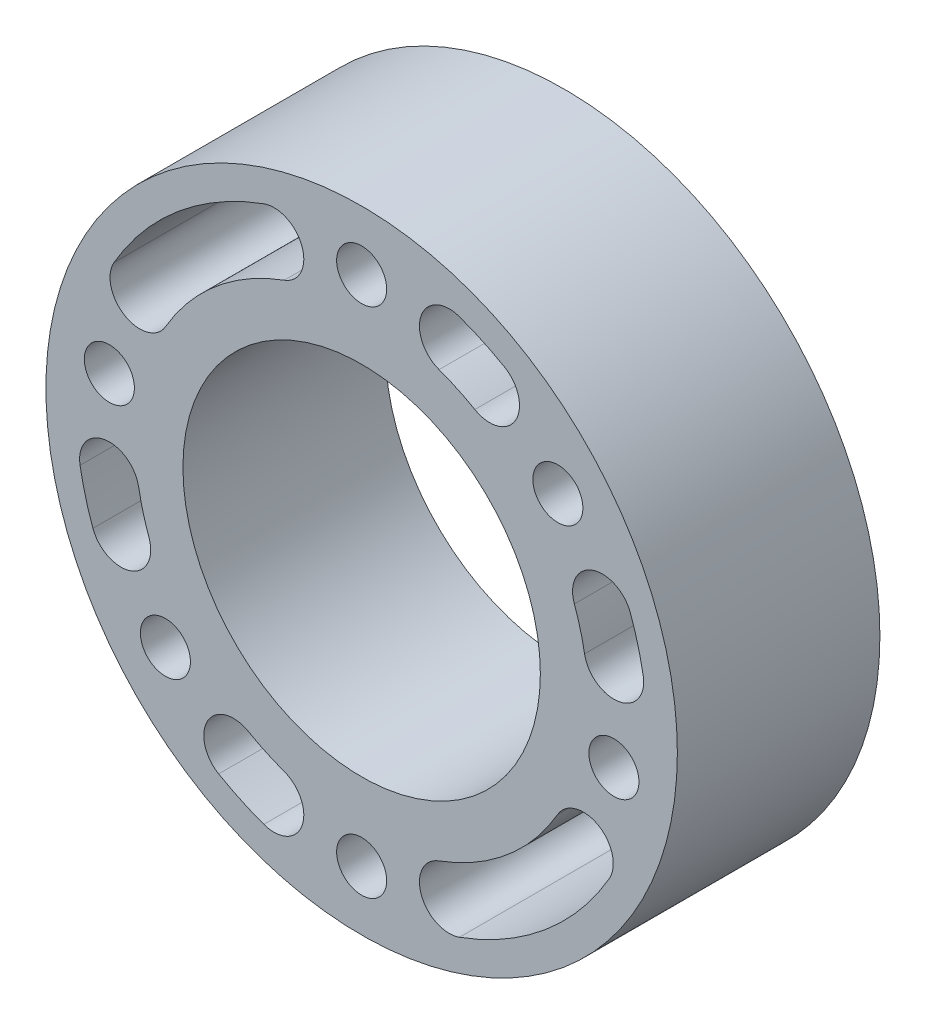
SolidWorks part; units mm, degrees
material "6061 合金"
ref_plane "前视基准面" through (0, 0, 0) normal (0, 0, 1) x (1, 0, 0)
ref_plane "上视基准面" through (0, 0, 0) normal (0, 1, 0) x (1, 0, 0)
ref_plane "右视基准面" through (0, 0, 0) normal (1, 0, 0) x (0, 0, -1)
sketch "草图1" plane through (0, 0, 0) normal (0, 0, 1) x (1, 0, 0)
  circle A0 centre (0, 0) radius 15
  circle A1 centre (0, 0) radius 26.5
  circle A2 centre (0, 0) radius 21.5 construction
  circle A3 centre (0, 21.5) radius 2.1
  circle A4 centre (16.47, 13.8199) radius 2.1
  circle A5 centre (21.1734, -3.7334) radius 2.1
  circle A6 centre (0, -21.5) radius 2.1
  circle A7 centre (-16.47, -13.8199) radius 2.1
  circle A8 centre (-21.1734, 3.7334) radius 2.1
  arc A9 (-18.6195, 10.75) -> (-7.3534, 20.2034) centre (0, 0) cw construction
  arc A10 (-8.2085, 22.5526) -> (-20.7846, 12) centre (0, 0) ccw
  arc A11 (-6.4984, 17.8542) -> (-16.4545, 9.5) centre (0, 0) ccw
  arc A12 (-6.4984, 17.8542) -> (-8.2085, 22.5526) centre (-7.3534, 20.2034) ccw
  arc A13 (-20.7846, 12) -> (-16.4545, 9.5) centre (-18.6195, 10.75) ccw
  arc A14 (7.3534, 20.2034) -> (10.75, 18.6195) centre (0, 0) cw construction
  arc A15 (12, 20.7846) -> (8.2085, 22.5526) centre (0, 0) ccw
  arc A16 (9.5, 16.4545) -> (6.4984, 17.8542) centre (0, 0) ccw
  arc A17 (9.5, 16.4545) -> (12, 20.7846) centre (10.75, 18.6195) ccw
  arc A18 (8.2085, 22.5526) -> (6.4984, 17.8542) centre (7.3534, 20.2034) ccw
  arc A19 (18.7113, 3.2993) -> (17.8542, 6.4984) centre (0, 0) ccw
  arc A20 (18.7113, 3.2993) -> (23.6354, 4.1676) centre (21.1734, 3.7334) ccw
  arc A21 (22.5526, 8.2085) -> (17.8542, 6.4984) centre (20.2034, 7.3534) ccw
  arc A22 (23.6354, 4.1676) -> (22.5526, 8.2085) centre (0, 0) ccw
  arc A23 (20.2034, 7.3534) -> (21.1734, 3.7334) centre (0, 0) cw construction
  arc A24 (6.4984, -17.8542) -> (16.4545, -9.5) centre (0, 0) ccw
  arc A25 (6.4984, -17.8542) -> (8.2085, -22.5526) centre (7.3534, -20.2034) ccw
  arc A26 (20.7846, -12) -> (16.4545, -9.5) centre (18.6195, -10.75) ccw
  arc A27 (8.2085, -22.5526) -> (20.7846, -12) centre (0, 0) ccw
  arc A28 (-9.5, -16.4545) -> (-6.4984, -17.8542) centre (0, 0) ccw
  arc A29 (-9.5, -16.4545) -> (-12, -20.7846) centre (-10.75, -18.6195) ccw
  arc A30 (-8.2085, -22.5526) -> (-6.4984, -17.8542) centre (-7.3534, -20.2034) ccw
  arc A31 (-12, -20.7846) -> (-8.2085, -22.5526) centre (0, 0) ccw
  arc A32 (-23.6354, -4.1676) -> (-22.5526, -8.2085) centre (0, 0) ccw
  arc A33 (-22.5526, -8.2085) -> (-17.8542, -6.4984) centre (-20.2034, -7.3534) ccw
  arc A34 (-18.7113, -3.2993) -> (-17.8542, -6.4984) centre (0, 0) ccw
  arc A35 (-18.7113, -3.2993) -> (-23.6354, -4.1676) centre (-21.1734, -3.7334) ccw
  arc A36 (18.6195, -10.75) -> (7.3534, -20.2034) centre (0, 0) cw construction
  arc A37 (-7.3534, -20.2034) -> (-10.75, -18.6195) centre (0, 0) cw construction
  arc A38 (-20.2034, -7.3534) -> (-21.1734, -3.7334) centre (0, 0) cw construction
  point P9 (-13.8199, 16.47)
  point P27 (9.0863, 19.4856)
  point P36 (20.7674, 5.5646)
  point P44 (13.8199, -16.47)
  point P51 (-9.0863, -19.4856)
  point P58 (-20.7674, -5.5646)
  dimension "D1" = 30
  dimension "D2" = 53
  dimension "D3" = 43
  dimension "D4" = 4.2
  dimension "D8" = 2.5
  dimension "D11" = 20
  dimension "D6" = 50
  dimension "D9" = 20
  dimension "D10" = 20
  dimension "D12" = 20
  dimension "D13" = 2
  dimension "D14" = 20
  dimension "D5" = 3
  dimension "D7" = 2
  dimension "D15" = 2
extrude "凸台-拉伸1" add sketch "草图1" along normal blind 17
